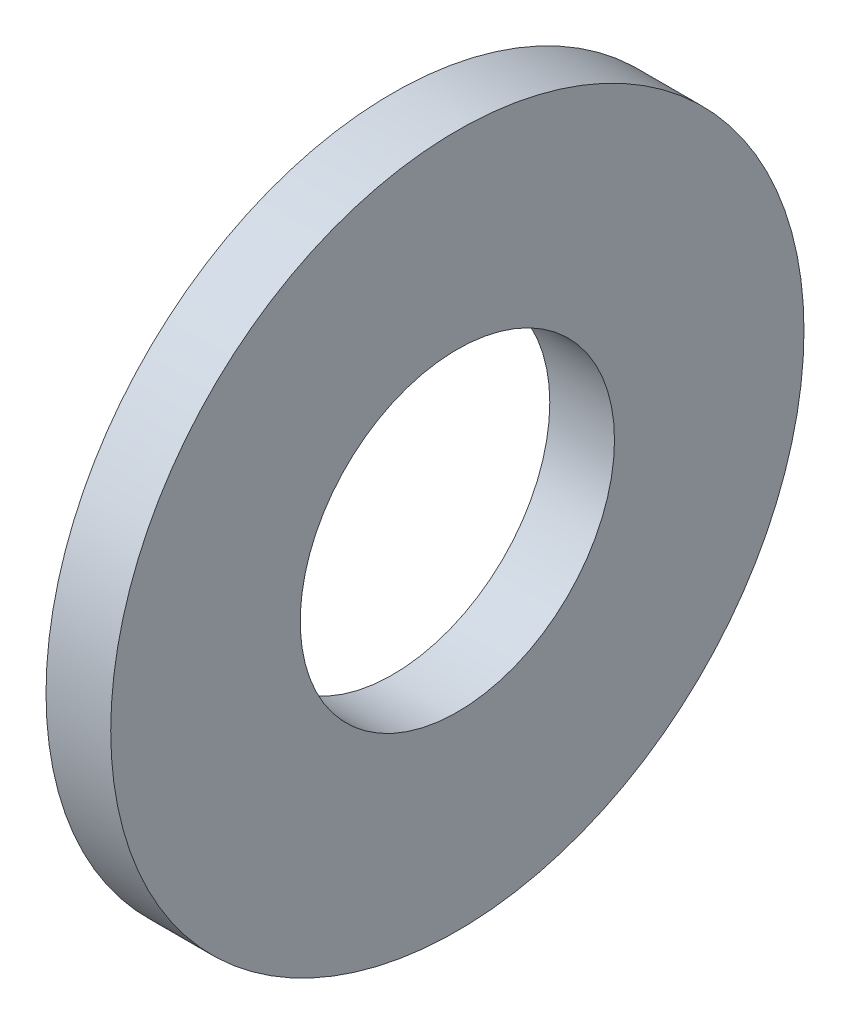
SolidWorks part; units mm, degrees
ref_plane "Front Plane" through (0, 0, 0) normal (0, 0, 1) x (1, 0, 0)
ref_plane "Top Plane" through (0, 0, 0) normal (0, 1, 0) x (1, 0, 0)
ref_plane "Right Plane" through (0, 0, 0) normal (1, 0, 0) x (0, 0, -1)
sketch "Sketch1" plane through (0, 0, 0) normal (1, 0, 0) x (0, 0, -1)
  circle A0 centre (0, 0) radius 2.159
  circle A1 centre (0, 0) radius 4.7625
  dimension "OD" = 4.318
  dimension "ID" = 9.525
extrude "Boss-Extrude1" add sketch "Sketch1" along normal blind 0.889
